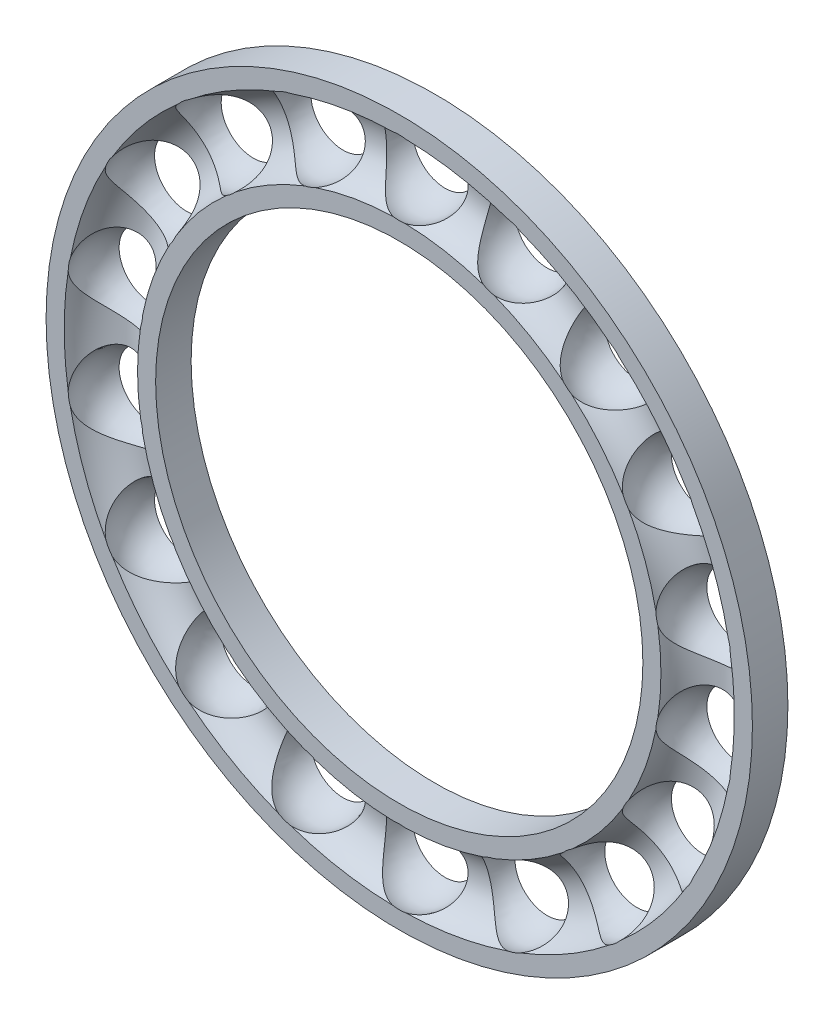
SolidWorks part; units mm, degrees
ref_plane "Plan de face" through (0, 0, 0) normal (0, 0, 1) x (1, 0, 0)
ref_plane "Plan de dessus" through (0, 0, 0) normal (0, 1, 0) x (1, 0, 0)
ref_plane "Plan de droite" through (0, 0, 0) normal (1, 0, 0) x (0, 0, -1)
sketch "Esquisse1" plane through (0, 0, 0) normal (0, 0, 1) x (1, 0, 0)
  line L0 (0, 23.375) -> (0, 16.125) construction
  line L1 (0, 19.75) -> (0, 0) construction
  circle A0 centre (0, 0) radius 23.375
  circle A1 centre (0, 0) radius 16.125
  dimension "D2" = 7.25
  dimension "D1" = 19.75
extrude "Boss.-Extru.1" add sketch "Esquisse1" along normal blind 3.54
ref_plane "Plan1" through (0, 0, 1.77) normal (0, 0, 1) x (1, 0, 0)
sketch "Esquisse3" plane through (0, 0, 1.77) normal (0, 0, 1) x (1, 0, 0)
  line L0 (0, 16.125) -> (0, 23.375) construction
  line L1 (0, 22.52) -> (0, 16.98)
  circle A0 centre (0, 0) radius 16.125 construction
  circle A1 centre (0, 0) radius 23.375 construction
  arc A2 (0, 16.98) -> (0, 22.52) centre (0, 19.75) ccw
  dimension "D1" = 2.77
  dimension "D2" = 19.75
revolve "Enlèvement de matière-Révolution1" cut sketch "Esquisse3" angle 360 about L0
pattern_circular "Répétition circulaire1" count 18 over 360 about axis through (0, 0, 0) along (0, 0, 1) of "Enlèvement de matière-Révolution1"
sketch "Esquisse4" plane through (0, 0, 0) normal (0, 0, -1) x (-1, 0, 0)
  circle A0 centre (0, 0) radius 16.125 construction
  circle A1 centre (0, 0) radius 23.375
  circle A2 centre (0, 0) radius 23.375
  circle A3 centre (0, 0) radius 16.125
  circle A4 centre (0, 19.75) radius 2.6307
  circle A5 centre (0, 19.75) radius 2.1307 construction
  circle A6 centre (6.7549, 18.5589) radius 2.6307
  circle A7 centre (0, 0) radius 16.125
  circle A8 centre (12.6951, 15.1294) radius 2.6307
  circle A9 centre (0, 0) radius 16.125
  circle A10 centre (17.104, 9.875) radius 2.6307
  circle A11 centre (0, 0) radius 16.125
  circle A12 centre (19.45, 3.4296) radius 2.6307
  circle A13 centre (0, 0) radius 16.125
  circle A14 centre (19.45, -3.4296) radius 2.6307
  circle A15 centre (0, 0) radius 16.125
  circle A16 centre (17.104, -9.875) radius 2.6307
  circle A17 centre (0, 0) radius 16.125
  circle A18 centre (12.6951, -15.1294) radius 2.6307
  circle A19 centre (0, 0) radius 16.125
  circle A20 centre (6.7549, -18.5589) radius 2.6307
  circle A21 centre (0, 0) radius 16.125
  circle A22 centre (0, -19.75) radius 2.6307
  circle A23 centre (0, 0) radius 16.125
  circle A24 centre (-6.7549, -18.5589) radius 2.6307
  circle A25 centre (0, 0) radius 16.125
  circle A26 centre (-12.6951, -15.1294) radius 2.6307
  circle A27 centre (0, 0) radius 16.125
  circle A28 centre (-17.104, -9.875) radius 2.6307
  circle A29 centre (0, 0) radius 16.125
  circle A30 centre (-19.45, -3.4296) radius 2.6307
  circle A31 centre (0, 0) radius 16.125
  circle A32 centre (-19.45, 3.4296) radius 2.6307
  circle A33 centre (0, 0) radius 16.125
  circle A34 centre (-17.104, 9.875) radius 2.6307
  circle A35 centre (0, 0) radius 16.125
  circle A36 centre (-12.6951, 15.1294) radius 2.6307
  circle A37 centre (0, 0) radius 16.125
  circle A38 centre (-6.7549, 18.5589) radius 2.6307
  circle A39 centre (0, 0) radius 16.125
  point P63 (0, 0)
  circle M25 centre (0, 0) radius 23.375
  circle M26 centre (0, 0) radius 16.125
  dimension "D2" = 0.5
  dimension "D1" = 0
  dimension "D3" = 18
extrude "Enlèv. mat.-Extru.1" cut sketch "Esquisse4" against normal blind 0.69 contours A38 A36 A34 A32 A30 A28 A26 A24 A22 A20 A18 A16 A14 A12 A10 A8 A6 A4 M25 M26
sketch "Esquisse5" plane through (0, 0, 0) normal (0, 1, 0) x (1, 0, 0)
  line L0 (16.125, -2.115) -> (23.375, -2.115) construction
  line L2 (16.125, -3.54) -> (16.125, -0.69) construction
  line L3 (23.375, -3.54) -> (23.375, -0.69) construction
  line L4 (19.75, -6.23) -> (19.75, -0.69) construction
  line L5 (23.375, -0.69) -> (-23.375, -0.69) construction
  line L6 (0, 0) -> (0, 4.0774) construction
  line L7 (19.75, -1.19) -> (19.75, -0.69) construction
  circle A0 centre (19.75, -3.71) radius 2.52
  point P16 (19.75, -2.115)
  dimension "D1" = 5.54
  dimension "D2" = 0.5
revolve "Enlèvement de matière-Révolution2" cut sketch "Esquisse5" angle 360 about L6
sketch "Esquisse6" plane through (0, 0, 3.54) normal (0, 0, 1) x (1, 0, 0)
  circle A0 centre (0, 0) radius 23.375 construction
  circle A1 centre (0, 0) radius 23.375
extrude "Enlèv. mat.-Extru.2" cut sketch "Esquisse6" against normal blind 0.5
